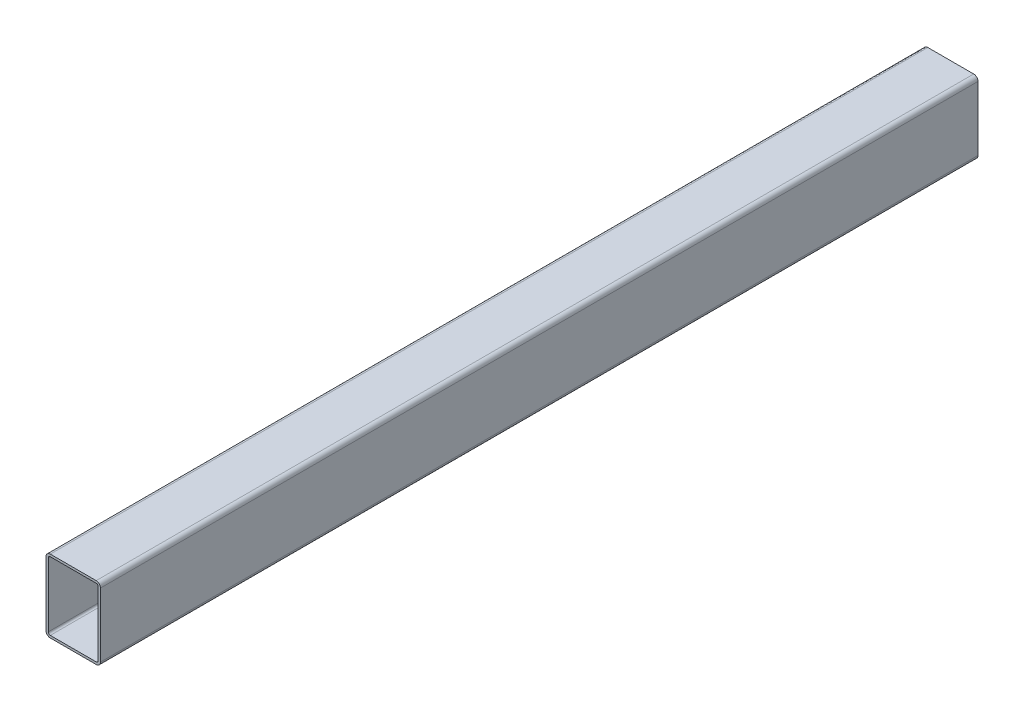
SolidWorks part; units mm, degrees
material "Plain Carbon Steel"
ref_plane "Front Plane" through (0, 0, 0) normal (0, 0, 1) x (1, 0, 0)
ref_plane "Top Plane" through (0, 0, 0) normal (0, 1, 0) x (1, 0, 0)
ref_plane "Right Plane" through (0, 0, 0) normal (1, 0, 0) x (0, 0, -1)
sketch "Sketch1" plane through (0, 0, 0) normal (0, 0, 1) x (1, 0, 0)
  line L0 (32.1, 47.625) -> (-32.1, 47.625)
  line L1 (32.1, -50.8) -> (-32.1, -50.8)
  line L2 (38.1, -44.8) -> (38.1, 44.8)
  line L3 (32.1, 50.8) -> (-32.1, 50.8)
  line L4 (-38.1, -44.8) -> (-38.1, 44.8)
  line L5 (38.1, -50.8) -> (-38.1, 50.8) construction
  line L6 (38.1, 50.8) -> (-38.1, -50.8) construction
  line L7 (-34.925, -44.8) -> (-34.925, 44.8)
  line L8 (32.1, -47.625) -> (-32.1, -47.625)
  line L9 (34.925, -44.8) -> (34.925, 44.8)
  arc A0 (-32.1, -50.8) -> (-38.1, -44.8) centre (-32.1, -44.8) cw
  arc A1 (32.1, -50.8) -> (38.1, -44.8) centre (32.1, -44.8) ccw
  arc A2 (38.1, 44.8) -> (32.1, 50.8) centre (32.1, 44.8) ccw
  arc A3 (-32.1, 50.8) -> (-38.1, 44.8) centre (-32.1, 44.8) ccw
  arc A4 (-32.1, 47.625) -> (-34.925, 44.8) centre (-32.1, 44.8) ccw
  arc A5 (-32.1, -47.625) -> (-34.925, -44.8) centre (-32.1, -44.8) cw
  arc A6 (32.1, -47.625) -> (34.925, -44.8) centre (32.1, -44.8) ccw
  arc A7 (34.925, 44.8) -> (32.1, 47.625) centre (32.1, 44.8) ccw
  point P0 (0, 0)
  dimension "D1" = 6
  dimension "D3" = 101.6
  dimension "D4" = 76.2
  dimension "D2" = 3.175
extrude "Boss-Extrude1" add sketch "Sketch1" along normal mid plane 1227
equation "\"M5_tap\"=4.2mm\t\t\t\t\t\t\t' Below you can do mesurements as follows: cm, mm, ft, in, m, "
equation "\"M5_clearence\"=5.5mm"
equation "\"M6_tap\"=5mm"
equation "\"M6_clearence\"=6.6mm"
equation "\"work_area_width\"=1100mm"
equation "\"work_area_depth\"=900mm"
equation "\"D3@Sketch1\"=\"steel_gantry_width\""
equation "\"D4@Sketch1\"=\"steel_gantry_height\""
equation "\"D1@Sketch1\"=\"steel_gantry_radius\""
equation "\"D2@Sketch1\"=\"steel_gantry_wall_thickness\""
equation "\"D1@Boss-Extrude1\"=\"work_area_width\" + \"steel_sides_height\" + \"steel_rollers_width\""
equation "\"steel_base_width\"=3in\t"
equation "\"steel_base_height\"=2in"
equation "\"steel_base_wall_thickness\"=0.125in"
equation "\"steel_base_radius\"=6mm"
equation "\"steel_sides_width\"=3in\t\t\t\t\t'this tube is rotated so flip width/height"
equation "\"steel_sides_height\"=2in\t\t\t\t'this tube is rotated so flip width/height"
equation "\"steel_sides_wall_thickness\"=0.125in"
equation "\"steel_sides_radius\"=6mm"
equation "\"steel_gantry_width\"=4in\t\t\t\t'this tube is rotated so flip width/height"
equation "\"steel_gantry_height\"=3in\t\t\t\t'this tube is rotated so flip width/height"
equation "\"steel_gantry_wall_thickness\"=0.125in"
equation "\"steel_gantry_radius\"=6mm"
equation "\"steel_rollers_width\"=3in"
equation "\"steel_rollers_height\"=2in\t\t\t\t'keep as low as possible as this increases how big plastic parts are"
equation "\"steel_rollers_wall_thickness\"=0.125in"
equation "\"steel_rollers_radius\"=6mm"
equation "\"steel_zbox_width\"=4in\t\t\t\t\t'if the gantry height (rotated) is too thick, a wider zbox is necessary"
equation "\"steel_zbox_height\"=2in\t\t\t\t\t'hole patteren changes as the zbox and gantry height (rotated) changes."
equation "\"steel_zbox_wall_thickness\"=0.125in"
equation "\"steel_zbox_radius\"=6mm"
